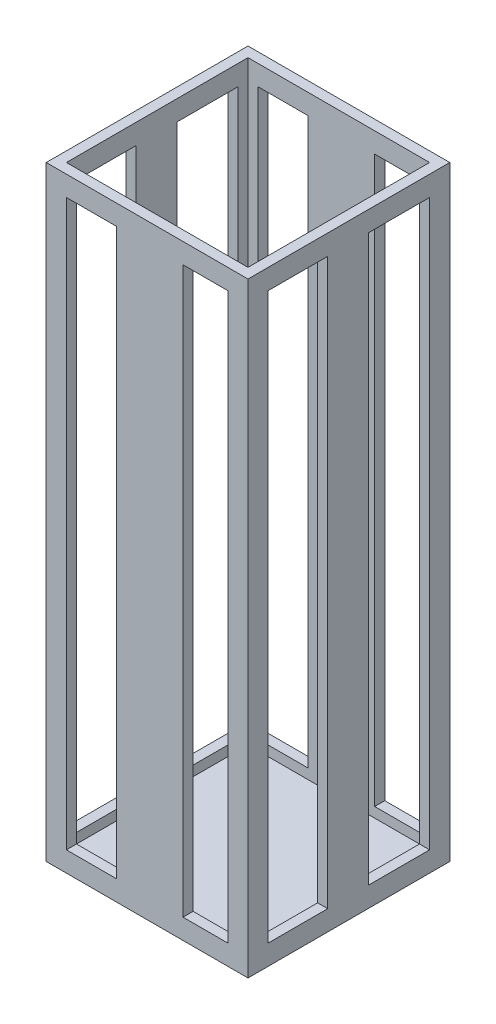
SolidWorks part; units mm, degrees
material "1060 Alloy"
ref_plane "Front Plane" through (0, 0, 0) normal (0, 0, 1) x (1, 0, 0)
ref_plane "Top Plane" through (0, 0, 0) normal (0, 1, 0) x (1, 0, 0)
ref_plane "Right Plane" through (0, 0, 0) normal (1, 0, 0) x (0, 0, -1)
other "Center of Mass"
sketch "Sketch1" plane through (0, 0, 0) normal (0, 1, 0) x (1, 0, 0)
  line L1 (0, 0) -> (100, 0)
  line L2 (0, 0) -> (0, 100)
  line L3 (0, 100) -> (100, 100)
  line L4 (100, 0) -> (100, 100)
extrude "Boss-Extrude1" add sketch "Sketch1" along normal blind 300
shell "Shell1" thickness 5
sketch "Sketch5" plane through (100, 0, 0) normal (1, 0, 0) x (0, 0, -1)
  line L5 (39.5203, 10) -> (59.8224, 10)
  line L6 (39.5203, 10) -> (39.5203, 290)
  line L7 (39.5203, 290) -> (59.8224, 290)
  line L8 (10, 10) -> (90, 10)
  line L9 (90, 10) -> (90, 290)
  line L10 (90, 290) -> (10, 290)
  line L11 (10, 290) -> (10, 10)
  line L12 (10, 10) -> (90, 10)
  line L13 (90, 10) -> (90, 290)
  line L14 (90, 290) -> (10, 290)
  line L15 (10, 290) -> (10, 10)
  line L16 (59.8224, 10) -> (59.8224, 290)
  dimension "D1" = 10
extrude "Cut-Extrude3" cut sketch "Sketch5" against normal through all contours L14 L15 L12 L6 | L16 L12 L13 L14
sketch "Sketch7" plane through (0, 0, -100) normal (0, 0, -1) x (-1, 0, 0)
  line L5 (-67.7885, 290) -> (-34.8577, 290)
  line L6 (-67.7885, 290) -> (-67.7885, 10)
  line L7 (-67.7885, 10) -> (-34.8577, 10)
  line L8 (-90, 10) -> (-10, 10)
  line L9 (-10, 10) -> (-10, 290)
  line L10 (-10, 290) -> (-90, 290)
  line L11 (-90, 290) -> (-90, 10)
  line L12 (-90, 10) -> (-10, 10)
  line L13 (-10, 10) -> (-10, 290)
  line L14 (-10, 290) -> (-90, 290)
  line L15 (-90, 290) -> (-90, 10)
  line L16 (-34.8577, 290) -> (-34.8577, 10)
  dimension "D1" = 10
extrude "Cut-Extrude4" cut sketch "Sketch7" against normal through all both and the other way through all contours L14 L15 L12 L6 | L14 L16 L12 L13
sketch "Sketch8" plane through (0, 0, -5) normal (0, 0, -1) x (-1, 0, 0)
  circle A0 centre (-52.4219, 126.4322) radius 2.2105
extrude "Boss-Extrude2" add sketch "Sketch8" along normal blind 1
sketch "Sketch9" plane through (0, 5, 0) normal (0, 1, 0) x (1, 0, 0)
  line L0 (0, 50) -> (100, 50)
  line L1 (0, 100) -> (0, 0) construction
  line L2 (100, 0) -> (100, 100) construction
  circle A0 centre (50, 50) radius 1
extrude "Boss-Extrude3" add sketch "Sketch9" along normal blind 2 contours L0 A0 | L0 A0
sketch "Sketch10" plane through (95, 0, 0) normal (-1, 0, 0) x (0, 0, 1)
  circle A0 centre (-50.458, 101.3517) radius 1
extrude "Boss-Extrude4" add sketch "Sketch10" along normal blind 2
